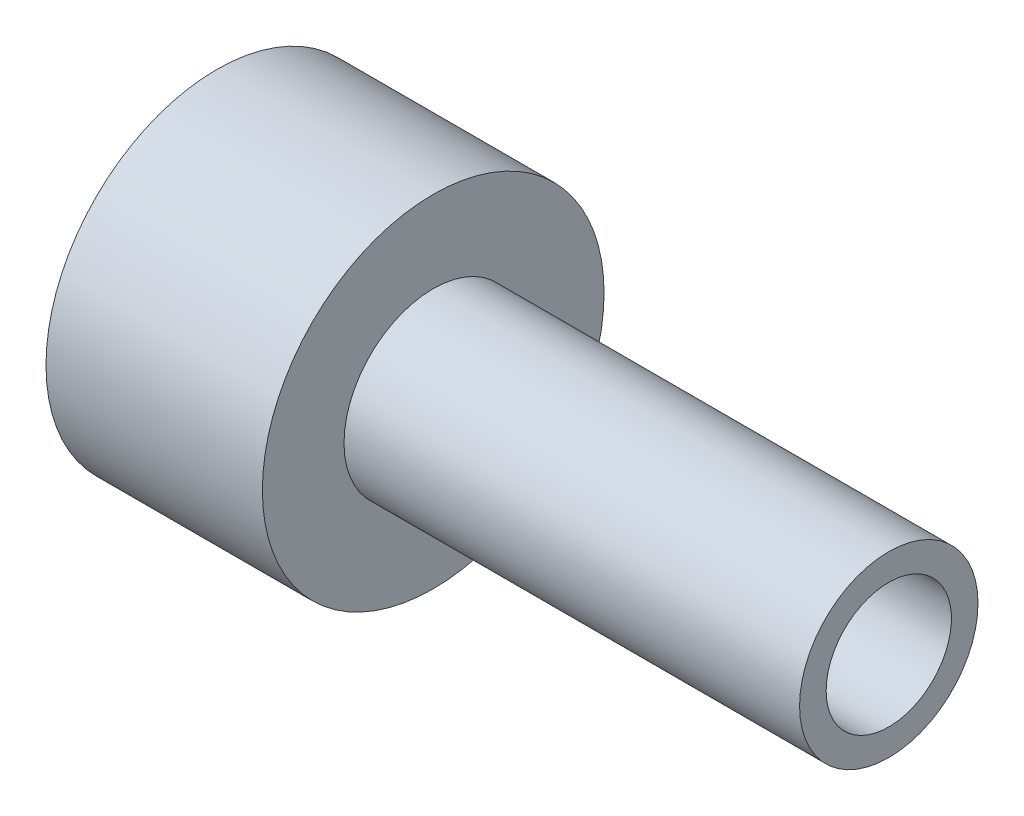
SolidWorks part; units mm, degrees
material "AISI Type 316L stainless steel"
ref_plane "Front Plane" through (0, 0, 0) normal (0, 0, 1) x (1, 0, 0)
ref_plane "Top Plane" through (0, 0, 0) normal (0, 1, 0) x (1, 0, 0)
ref_plane "Right Plane" through (0, 0, 0) normal (1, 0, 0) x (0, 0, -1)
sketch "Axial profile (mm)" plane through (0, 0, 0) normal (0, 0, 1) x (1, 0, 0)
  line L0 (-110, 0) -> (75, 0) construction
  line L1 (8, 1.65) -> (25.7, 1.65)
  line L2 (25.7, 1.65) -> (25.7, 2.35)
  line L3 (25.7, 2.35) -> (13.7, 2.35)
  line L4 (13.7, 2.35) -> (13.7, 4.5)
  line L5 (13.7, 4.5) -> (8, 4.5)
  line L6 (8, 4.5) -> (8, 1.65)
revolve "Full revolution" add sketch "Axial profile (mm)" angle 360 about L0
